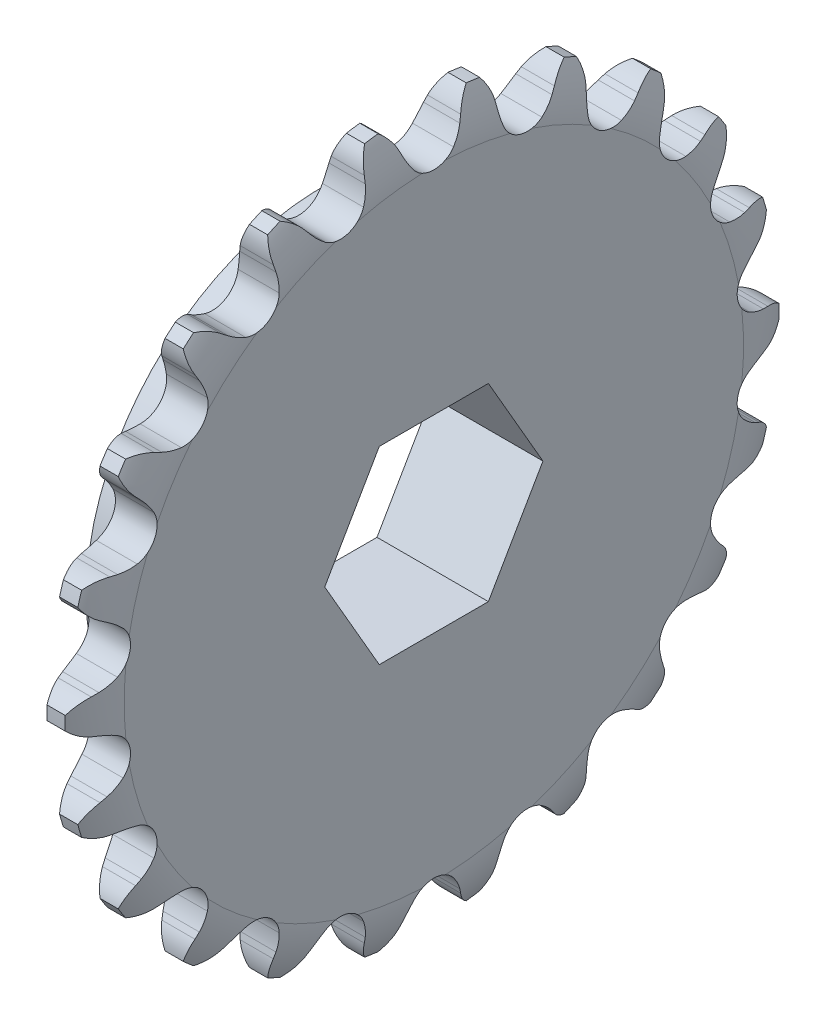
SolidWorks part; units mm, degrees
ref_plane "Plane1" through (0, 0, 0) normal (0, 0, 1) x (1, 0, 0)
ref_plane "Plane2" through (0, 0, 0) normal (0, 1, 0) x (1, 0, 0)
ref_plane "Plane3" through (0, 0, 0) normal (1, 0, 0) x (0, 0, -1)
sketch "Clipboard" plane through (0, 0, 0) normal (0, 1, 0) x (1, 0, 0)
  line L0 (0, 0) -> (5.8876, -2.3788)
  line L1 (-15, 0) -> (100, 0) construction
  line L2 (0, 0) -> (-0.5218, 0.5897)
  line L3 (0, 0) -> (-2.9658, 1.1335)
  line L4 (0, 0) -> (2.9438, 1.1894)
  line L5 (0, 0) -> (-9.6384, -3.5949)
  line L6 (0, 0) -> (-2.3214, -1.5662)
  line L7 (-0.5218, 0.5897) -> (8.9475, 4.6092)
  line L8 (-76.2, 38.1) -> (-65.4837, 38.1)
  line L9 (-73.2057, 38.5609) -> (-73.0533, 38.5634)
  line L10 (-73.0533, 76.1892) -> (-66.6525, 76.1892)
  circle A0 centre (0, 0) radius 1.651
  circle A1 centre (0, 0) radius 15.875
  circle A2 centre (0, 0) radius 15.875
  dimension "Dr" = 3.302
  dimension "MHD" = 31.75
  dimension "Hub_dia" = 31.75
  dimension "Num_teeth" = 22
  dimension "Pitch" = 6.35
  dimension "Width" = 3.175
  dimension "Chamfer_wid" = 0.7874
  dimension "Chamfer_dep" = 3.175
  dimension "Overall_len" = 10.287
  dimension "Show_teeth" = 22
  dimension "Thickness" = 2.8004
  dimension "OAL" = 10.2871
  dimension "T_dim" = 10.7163
  dimension "Width_const" = 0.1524
  dimension "Width_factor" = 0.93
  dimension "Num_strands" = 1
  dimension "Transv_pitch" = 6.4008
sketch "BasProSke" plane through (0, 0, 0) normal (0, 1, 0) x (1, 0, 0)
  line L0 (-10, 0) -> (60, 0) construction
  line L1 (0, 0) -> (0, 20.8126)
  line L2 (0, 0) -> (2.8004, 0)
  line L3 (2.8004, 0) -> (2.8003, 20.8126)
  line L4 (2.0129, 23.9876) -> (0.7874, 23.9876)
  arc A0 (0, 20.8126) -> (0.7874, 23.9876) centre (6.7949, 20.8126) cw
  arc A1 (2.8003, 20.8126) -> (2.0129, 23.9876) centre (-3.9946, 20.8126) ccw
  dimension "D1" = 6.7949
  dimension "G1" = 0.7874
  dimension "G2" = 0.7874
  dimension "H2" = 3.175
  dimension "Diameter" = 47.9752
  dimension "H1" = 3.175
  dimension "Thickness" = 2.8004
revolve "Base-Revolve" add sketch "BasProSke" angle 360 about L0
sketch "GrvSke" plane through (0, 0, 0) normal (0, 1, 0) x (1, 0, 0)
  line L0 (2.8003, 20.8126) -> (2.8003, 18.5266)
  line L1 (2.8003, 18.5266) -> (6.4008, 18.5266)
  line L2 (6.4008, 18.5266) -> (6.4008, 20.8126)
  line L3 (2.0129, 23.9876) -> (7.1882, 23.9876)
  line L4 (4.6006, 0) -> (4.6006, 52.07) construction
  line L5 (-10, 0) -> (60, 0) construction
  line L6 (0, 0) -> (35.56, 0) construction
  arc A0 (6.4008, 20.8126) -> (7.1882, 23.9876) centre (13.1957, 20.8126) cw
  arc A1 (2.8003, 20.8126) -> (2.0129, 23.9876) centre (-3.9946, 20.8126) ccw
  dimension "Diameter" = 47.9752
  dimension "H1" = 3.175
  dimension "Grv_diam" = 37.0532
  dimension "Grv_width" = 3.6004
  dimension "Offset" = 4.6006
  dimension "G1" = 0.7874
revolve "Groove" [suppressed] cut sketch "GrvSke" angle 360 about L6
pattern_linear "Grooves" [suppressed]
sketch "TooCutSke" plane through (0, 0, 0) normal (1, 0, 0) x (0, 0, -1)
  line L0 (1.9259, 22.2816) -> (2.0857, 22.6717)
  line L1 (0, 0) -> (0, 107) construction
  line L2 (0, 22.3097) -> (-10, 22.3097) construction
  line L3 (-1.9259, 22.2816) -> (-2.0857, 22.6717)
  arc A0 (1.3425, 21.2711) -> (1.9259, 22.2816) centre (-2.0893, 23.9261) ccw
  arc A1 (1.3425, 21.2711) -> (-1.3425, 21.2711) centre (0, 22.3097) cw
  arc A2 (2.0857, 22.6717) -> (4.5757, 24.3426) centre (4.5757, 21.6518) cw
  arc A3 (-1.3425, 21.2711) -> (-1.9259, 22.2816) centre (2.0893, 23.9261) cw
  arc A4 (-2.0857, 22.6717) -> (-4.5757, 24.3426) centre (-4.5757, 21.6518) ccw
  arc A5 (4.5757, 24.3426) -> (-4.5757, 24.3426) centre (0, 0) ccw
  dimension "R" = 1.6974
  dimension "E" = 4.339
  dimension "F" = 2.6908
  dimension "Pitch_radius" = 22.3097
  dimension "W" = 4.5757
  dimension "V" = 0.6579
  dimension "A" = 37.727
  dimension "B" = 15.455
extrude "ToothCut" cut sketch "TooCutSke" along normal through all
pattern_circular "TeethCuts" count 22 every 16.364 about axis through (-10, 0, 0) along (1, 0, 0) of "ToothCut"
sketch "HubNeaOneSke" plane through (0, 0, 0) normal (-1, 0, 0) x (0, 0, 1)
  circle A0 centre (0, 0) radius 15.875
  dimension "Diameter" = 31.75
extrude "HubNearOne" add sketch "HubNeaOneSke" along normal blind 7.4867
sketch "HubNeaBotSke" plane through (0, 0, 0) normal (-1, 0, 0) x (0, 0, 1)
  circle A0 centre (0, 0) radius 15.875
  dimension "Diameter" = 31.75
extrude "HubNearBoth" [suppressed] add sketch "HubNeaBotSke" along normal blind 3.7434
ref_plane "FarPln" through (2.8004, 0, 0) normal (1, 0, 0) x (0, 0, -1)
sketch "HubFarSke" plane through (2.8004, 0, 0) normal (1, 0, 0) x (0, 0, -1)
  circle A0 centre (0, 0) radius 15.875
  dimension "Diameter" = 31.75
extrude "HubFar" [suppressed] add sketch "HubFarSke" along normal blind 3.7434
sketch "BorSke" plane through (0, 0, 0) normal (1, 0, 0) x (0, 0, -1)
  circle A0 centre (0, 0) radius 4.7625
  dimension "Diameter" = 9.525
extrude "Bore" cut sketch "BorSke" along normal mid plane 20.5741
sketch "KeySke" plane through (0, 0, 0) normal (1, 0, 0) x (0, 0, -1)
  line L0 (-1.1913, 0) -> (-1.1913, 5.9538)
  line L1 (-1.1913, 5.9538) -> (1.1913, 5.9538)
  line L2 (1.1913, 5.9538) -> (1.1913, 0)
  line L3 (0, 0) -> (0, 34) construction
  line L4 (-1.1913, 0) -> (1.1913, 0)
  dimension "Offset" = 5.9538
  dimension "Width" = 2.3825
extrude "Keyway" [suppressed] cut sketch "KeySke" along normal mid plane 20.5741
pattern_circular "Keyway2" [suppressed] count 2 every 90 about axis through (-10, 0, 0) along (1, 0, 0)
sketch "Sketch1" plane through (-7.4867, 0, 0) normal (-1, 0, 0) x (0, 0, 1)
  line L1 (-7.3323, 0) -> (-3.6662, -6.35)
  line L2 (-3.6662, -6.35) -> (3.6662, -6.35)
  line L3 (3.6662, -6.35) -> (7.3323, 0)
  line L4 (7.3323, 0) -> (3.6662, 6.35)
  line L5 (3.6662, 6.35) -> (-3.6662, 6.35)
  line L6 (-3.6662, 6.35) -> (-7.3323, 0)
  circle A0 centre (0, 0) radius 6.35 construction
  dimension "D1" = 12.7
extrude "Cut-Extrude1" cut sketch "Sketch1" against normal through all
sketch "Sketch2" plane through (-7.4867, 0, 0) normal (-1, 0, 0) x (0, 0, 1)
  circle A0 centre (0, 0) radius 15.875
  circle A1 centre (0, 0) radius 15.875 construction
extrude "Cut-Extrude2" cut sketch "Sketch2" against normal up to surface (2.8003 mm away)
equation "\"Num_teeth@Clipboard\" = int( \"Num_teeth@Clipboard\" )"
equation "\"Num_teeth@Clipboard\" = ((sgn( \"Num_teeth@Clipboard\" - 5.0)+1)*( \"Num_teeth@Clipboard\" - 5.0))/2 +5.0"
equation "\"Num_teeth@Clipboard\" = ((sgn( \"Num_teeth@Clipboard\" - 200.0)-1)*( \"Num_teeth@Clipboard\" - 200.0))/-2 +200.0"
equation "\"MHD@Clipboard\" = \"Pitch@Clipboard\" * (1.0 / tan(3.14159265 / \"Num_teeth@Clipboard\" ) - 1.0) - 0.03"
equation "\"Thickness@Clipboard\"  = \"Width@Clipboard\" * \"Width_factor@Clipboard\" - \"Width_const@Clipboard\" + (\"Num_strands@Clipboard\" - 1) * \"Transv_pitch@Clipboard\""
equation "\"OAL@Clipboard\" = \"Thickness@Clipboard\""
equation "\"MHD@Clipboard\" = ((sgn( \"MHD@Clipboard\" - \"Hub_dia@Clipboard\" )-1)*( \"MHD@Clipboard\" - \"Hub_dia@Clipboard\" ))/-2+ \"Hub_dia@Clipboard\""
equation "\"OAL@Clipboard\" = ((sgn( \"OAL@Clipboard\" - \"Overall_len@Clipboard\" )+1)*( \"OAL@Clipboard\" - \"Overall_len@Clipboard\" ))/2 + \"Overall_len@Clipboard\" + 0.000002"
equation "\"Num_teeth@TeethCuts\" = int( \"Show_teeth@Clipboard\" ) + 1"
equation "\"Num_teeth@TeethCuts\" = ((sgn( \"Num_teeth@TeethCuts\" - \"Num_teeth@Clipboard\" )-1)*( \"Num_teeth@TeethCuts\" - \"Num_teeth@Clipboard\" ))/-2+ \"Num_teeth@Clipboard\""
equation "\"Num_teeth@TeethCuts\" = ((sgn( \"Num_teeth@TeethCuts\" - 2.0)+1)*( \"Num_teeth@TeethCuts\" - 2.0))/2 +2.0"
equation "\"Angle@TeethCuts\" = 360.0 / \"Num_teeth@Clipboard\""
equation "\"Pitch_radius@TooCutSke\" = ( \"Pitch@Clipboard\" / 2.0) / sin(3.14159265 / \"Num_teeth@Clipboard\" )  'ma"
equation "\"R@TooCutSke\"  = \"Dr@Clipboard\" * 0.5025 + 0.0015"
equation "\"A@TooCutSke\" = 35.0 + (60.0 / \"Num_teeth@Clipboard\")"
equation "\"E@TooCutSke\"  = \"Dr@Clipboard\" * 1.3025 + 0.0015"
equation "\"B@TooCutSke\"  = 18.0 - (56.0 / \"Num_teeth@Clipboard\" )"
equation "\"W@TooCutSke\" = 1.4 * \"Dr@Clipboard\" * cos(3.14159265 / \"Num_teeth@Clipboard\" )"
equation "\"V@TooCutSke\" = 1.4 * \"Dr@Clipboard\" * sin(3.14159265 / \"Num_teeth@Clipboard\" )"
equation "\"Diameter@BasProSke\" = 2.0 * ( (0.3 * \"Pitch@Clipboard\" ) +  \"Pitch@Clipboard\" / 2.0 / tan(3.14159265 / \"Num_teeth@Clipboard\" ))"
equation "\"Thickness@BasProSke\"  = \"Thickness@Clipboard\""
equation "\"G1@BasProSke\" =  \"Chamfer_wid@Clipboard\""
equation "\"G2@BasProSke\" =  \"Chamfer_wid@Clipboard\""
equation "\"H1@BasProSke\" =  \"Chamfer_dep@Clipboard\""
equation "\"H2@BasProSke\" =  \"Chamfer_dep@Clipboard\""
equation "\"Diameter@GrvSke\" = \"Diameter@BasProSke\""
equation "\"G1@GrvSke\" = \"Chamfer_wid@Clipboard\""
equation "\"H1@GrvSke\" = \"Chamfer_dep@Clipboard\""
equation "\"Grv_diam@GrvSke\" =  \"Pitch@Clipboard\" * (1.0 / tan(3.14159265 / \"Num_teeth@Clipboard\" ) - 1.0) - 0.03"
equation "\"Grv_width@GrvSke\" =  \"Transv_pitch@Clipboard\" - ( \"Width@Clipboard\" * \"Width_factor@Clipboard\" - \"Width_const@Clipboard\" )"
equation "\"Offset@GrvSke\" = \"Grv_width@GrvSke\" / 2.0 + ( \"Width@Clipboard\" * \"Width_factor@Clipboard\" - \"Width_const@Clipboard\" )"
equation "\"Offset@Grooves\" = \"Transv_pitch@Clipboard\""
equation "\"Num_grvs@Grooves\" = \"Num_strands@Clipboard\""
equation "\"Num_grvs@Grooves\" = \"Num_grvs@Grooves\" - 1 * sgn( \"Num_grvs@Grooves\" -1)"
equation "\"Diameter@HubNeaOneSke\" = \"MHD@Clipboard\""
equation "\"Length@HubNearOne\" = \"OAL@Clipboard\" - \"Thickness@BasProSke\""
equation "\"Diameter@HubNeaBotSke\" = \"MHD@Clipboard\""
equation "\"Length@HubNearBoth\" = ( \"OAL@Clipboard\" - \"Thickness@BasProSke\" ) / 2.0"
equation "\"Thickness@FarPln\" = \"Thickness@BasProSke\""
equation "\"Diameter@HubFarSke\" = \"MHD@Clipboard\""
equation "\"Length@HubFar\" = ( \"OAL@Clipboard\" - \"Thickness@BasProSke\" ) / 2.0"
equation "\"D1@Bore\" = \"OAL@Clipboard\" * 2.0"
equation "\"D1@Keyway\" = \"OAL@Clipboard\" * 2.0"
equation "\"Offset@KeySke\" = \"T_dim@Clipboard\" - \"Diameter@BorSke\" / 2.0"
